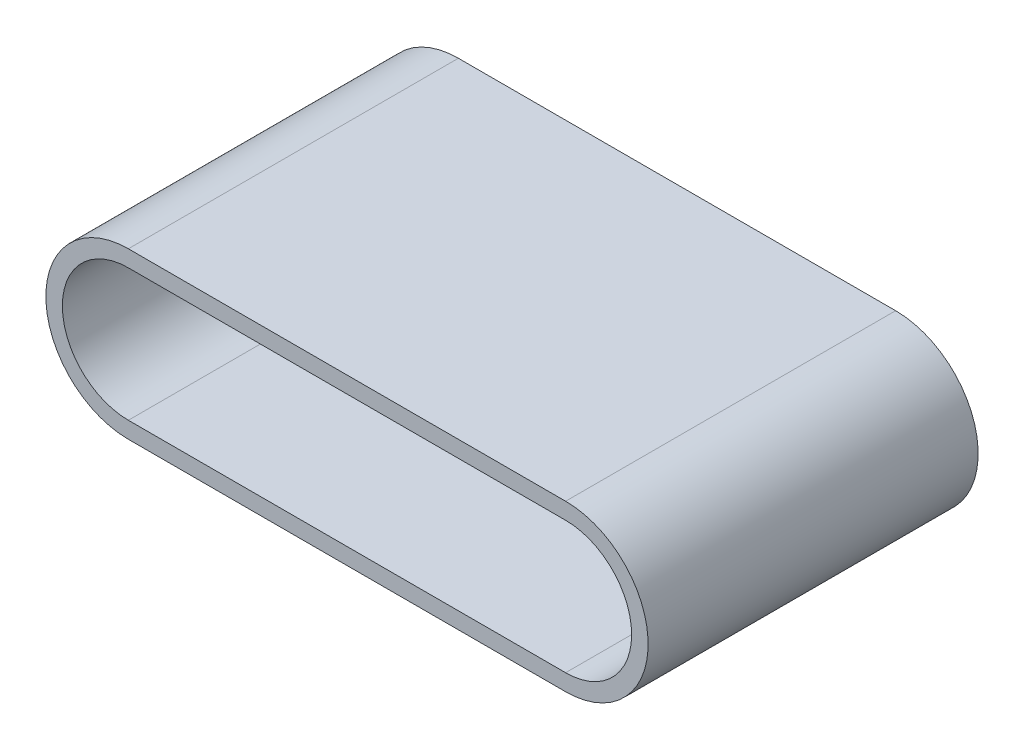
SolidWorks part; units mm, degrees
ref_plane "前视基准面" through (0, 0, 0) normal (0, 0, 1) x (1, 0, 0)
ref_plane "上视基准面" through (0, 0, 0) normal (0, 1, 0) x (1, 0, 0)
ref_plane "右视基准面" through (0, 0, 0) normal (1, 0, 0) x (0, 0, -1)
sketch "草图2" plane through (0, 0, 0) normal (0, 0, 1) x (1, 0, 0)
  line L0 (0, 0) -> (1, 0) construction
  line L1 (0, 0) -> (0, 1) construction
  line L2 (57.4342, 40) -> (322.4342, 40)
  line L3 (322.4342, -40) -> (57.4342, -40)
  arc A0 (57.4342, -40) -> (57.4342, 40) centre (57.4342, 0) cw
  arc A1 (322.4342, 40) -> (322.4342, -40) centre (322.4342, 0) cw
extrude "拉伸-薄壁1" add sketch "草图2" along normal mid plane 200 thin thin type one direction wall 10
